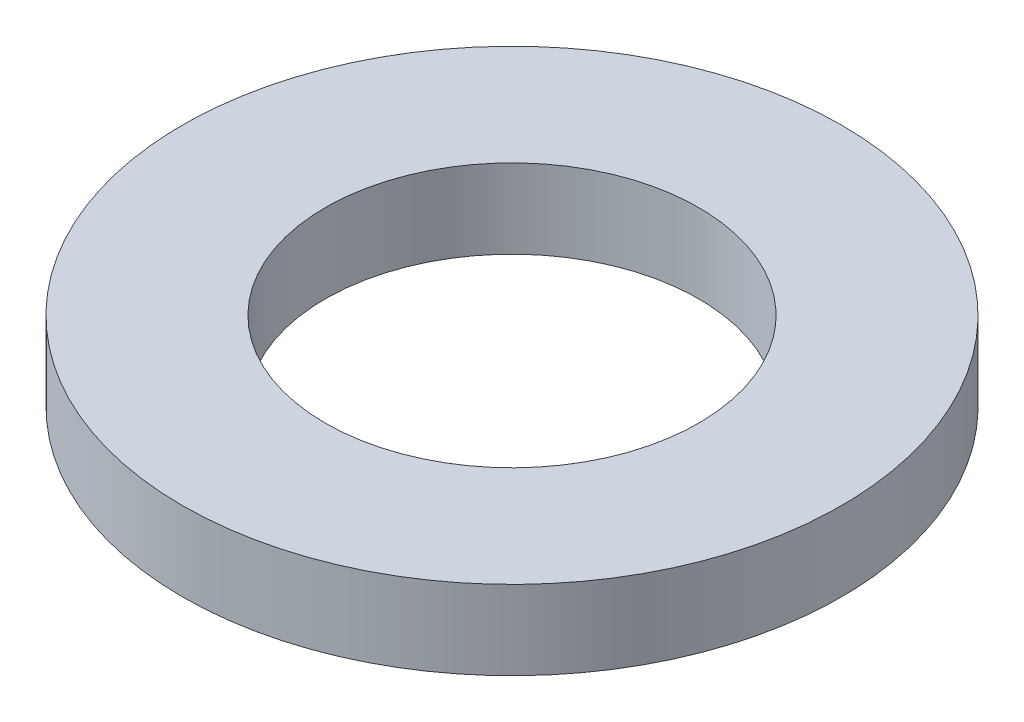
SolidWorks part; units mm, degrees
ref_plane "Front Plane" through (0, 0, 0) normal (0, 0, 1) x (1, 0, 0)
ref_plane "Top Plane" through (0, 0, 0) normal (0, 1, 0) x (1, 0, 0)
ref_plane "Right Plane" through (0, 0, 0) normal (1, 0, 0) x (0, 0, -1)
sketch "Sketch1" plane through (0, 0, 0) normal (0, 1, 0) x (1, 0, 0)
  circle A0 centre (0, 0) radius 4.25
  circle A1 centre (0, 0) radius 7.5
  dimension "D1" = 8.5
  dimension "D2" = 15
extrude "Boss-Extrude1" add sketch "Sketch1" along normal blind 1.8
